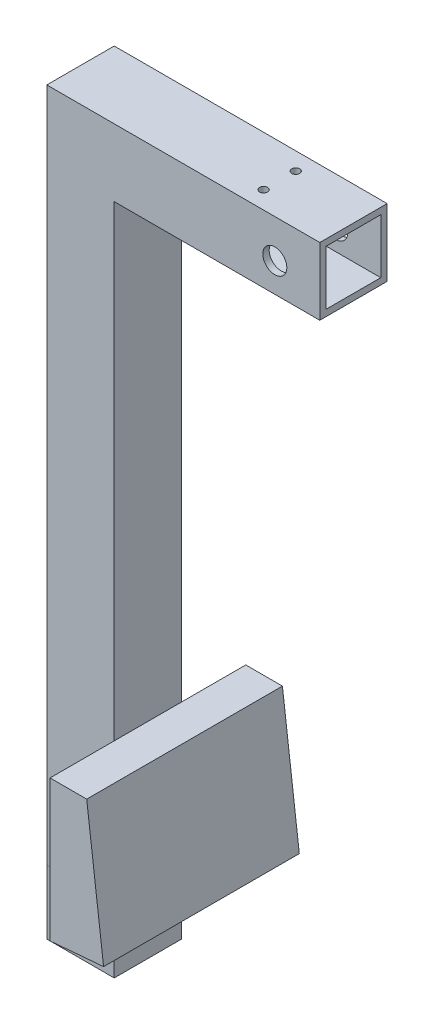
SolidWorks part; units mm, degrees
ref_plane "Front Plane" through (0, 0, 0) normal (0, 0, 1) x (1, 0, 0)
ref_plane "Top Plane" through (0, 0, 0) normal (0, 1, 0) x (1, 0, 0)
ref_plane "Right Plane" through (0, 0, 0) normal (1, 0, 0) x (0, 0, -1)
ref_plane "Plane1" through (0, -137.16, 0) normal (0, 1, 0) x (-1, 0, 0)
sketch "Sketch1" plane through (0, 0, 0) normal (0, 0, 1) x (1, 0, 0)
  line L1 (-598.0698, -137.16) -> (-598.0698, 115.0709)
  line L2 (55, -137.16) -> (-55, -137.16) construction
  line L3 (-598.0698, 115.0709) -> (-505.2048, 115.0709)
  point P0 (-523.0107, 115.0709)
  point P7 (-598.0698, 115.0709)
ref_point "Point1"
sketch "Sketch3" plane through (0, -137.16, 0) normal (0, 1, 0) x (-1, 0, 0)
  line L0 (610.7039, 10.795) -> (589.1139, 10.795)
  line L1 (613.2439, -13.335) -> (586.5739, -13.335)
  line L2 (613.2439, -13.335) -> (613.2439, 13.335)
  line L3 (613.2439, 13.335) -> (586.5739, 13.335)
  line L4 (586.5739, -13.335) -> (586.5739, 13.335)
  line L5 (613.2439, -13.335) -> (586.5739, 13.335) construction
  line L6 (613.2439, 13.335) -> (586.5739, -13.335) construction
  line L7 (589.1139, -10.795) -> (589.1139, 10.795)
  line L8 (610.7039, -10.795) -> (589.1139, -10.795)
  line L9 (610.7039, -10.795) -> (610.7039, 10.795)
  dimension "D1" = 2.54
sweep "Sweep1" add profiles "Sketch3" path "Sketch1"
sketch "Sketch5" plane through (0, -137.16, 0) normal (0, 1, 0) x (-1, 0, 0)
  line L1 (587.3376, 30.689) -> (559.7469, 30.689)
  line L2 (587.3376, 30.689) -> (587.3376, -38.3843)
  line L3 (587.3376, -38.3843) -> (559.7469, -38.3843)
  line L4 (559.7469, 30.689) -> (559.7469, -38.3843)
sketch "Sketch7" plane through (0, 0, -13.335) normal (0, 0, -1) x (-1, 0, 0)
  line L0 (586.5739, -137.16) -> (565.3801, -135.3697)
  line L1 (565.3801, -135.3697) -> (572.0627, -81.2784)
  line L2 (572.0627, -81.2784) -> (586.5739, -81.2784)
  line L3 (586.5739, 103.575) -> (586.5739, -137.16) construction
  line L4 (586.5739, -81.2784) -> (586.5739, -137.16)
extrude "Boss-Extrude1" add sketch "Sketch7" against normal blind 52.07 and the other way blind 25.4
sketch "Sketch8" plane through (0, -137.16, 0) normal (0, -1, 0) x (1, 0, 0)
  line L1 (-613.2439, -13.335) -> (-586.5739, -13.335)
  line L2 (-613.2439, -13.335) -> (-613.2439, 13.335)
  line L3 (-613.2439, 13.335) -> (-586.5739, 13.335)
  line L4 (-586.5739, -13.335) -> (-586.5739, 13.335)
  line L5 (-610.7039, -10.795) -> (-589.1139, -10.795)
  line L6 (-610.7039, -10.795) -> (-610.7039, 10.795)
  line L7 (-610.7039, 10.795) -> (-589.1139, 10.795)
  line L8 (-589.1139, -10.795) -> (-589.1139, 10.795)
extrude "Boss-Extrude2" add sketch "Sketch8" along normal blind 25.4 separate body
sketch "Sketch9" plane through (0, 0, -13.335) normal (0, 0, -1) x (-1, 0, 0)
  line L1 (505.2048, 130.245) -> (505.2048, 103.575) construction
  circle A0 centre (523.0107, 115.0709) radius 4.7625
extrude "Cut-Extrude1" cut sketch "Sketch9" against normal through all
sketch "Sketch10" plane through (0, 130.245, 0) normal (0, 1, 0) x (1, 0, 0)
  line L0 (-505.2048, -13.335) -> (-505.2048, 13.335) construction
  line L1 (-505.2048, 0) -> (-534.4148, 0) construction
  circle A0 centre (-534.4148, 6.35) radius 1.5875
  circle A1 centre (-534.4148, -6.35) radius 1.5875
  dimension "D1" = 3.175
  dimension "D2" = 29.21
  dimension "D3" = 6.35
extrude "Cut-Extrude2" cut sketch "Sketch10" against normal through all
